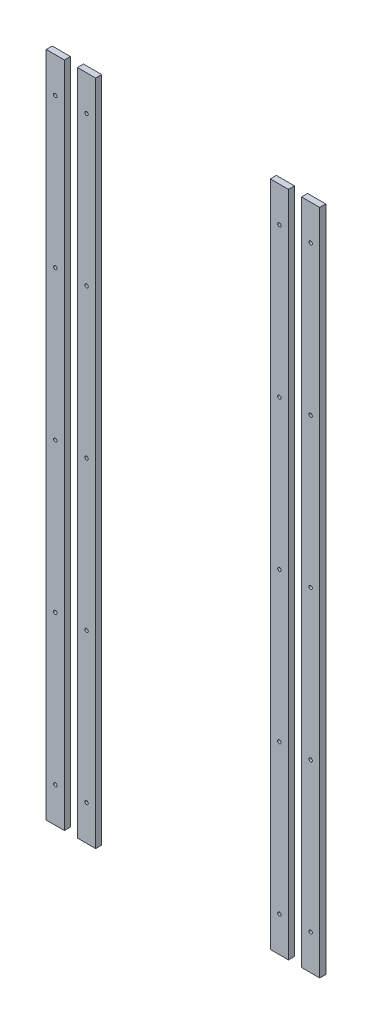
SolidWorks part; units mm, degrees
ref_plane "Спереди" through (0, 0, 0) normal (0, 0, 1) x (1, 0, 0)
ref_plane "Сверху" through (0, 0, 0) normal (0, 1, 0) x (1, 0, 0)
ref_plane "Справа" through (0, 0, 0) normal (1, 0, 0) x (0, 0, -1)
sketch "Четыре_направляющие_эскиз" plane through (0, 0, 0) normal (0, 0, 1) x (1, 0, 0)
  line L0 (315.5, -427) -> (333.5, -427)
  line L1 (333.5, -427) -> (333.5, 235)
  line L2 (333.5, 235) -> (315.5, 235)
  line L3 (315.5, 235) -> (315.5, -427)
  line L4 (346.5, -427) -> (364.5, -427)
  line L5 (364.5, -427) -> (364.5, 235)
  line L6 (364.5, 235) -> (346.5, 235)
  line L7 (346.5, 235) -> (346.5, -427)
  line L8 (537.8, -427) -> (555.8, -427)
  line L9 (555.8, -427) -> (555.8, 235)
  line L10 (555.8, 235) -> (537.8, 235)
  line L11 (537.8, 235) -> (537.8, -427)
  line L12 (568.8, -427) -> (586.8, -427)
  line L13 (586.8, -427) -> (586.8, 235)
  line L14 (586.8, 235) -> (568.8, 235)
  line L15 (568.8, 235) -> (568.8, -427)
  dimension "X001" = 315.5
  dimension "X002" = 333.5
  dimension "X003" = 346.5
  dimension "X004" = 364.5
  dimension "X005" = 537.8
  dimension "X006" = 555.8
  dimension "X007" = 568.8
  dimension "X008" = 586.8
  dimension "Y001" = 427
  dimension "Y002" = 235
extrude "Четыре_направляющие_6мм" add sketch "Четыре_направляющие_эскиз" along normal blind 6
sketch "Крепление_направляющих_М3_эскиз" plane through (0, 0, 0) normal (0, 0, 1) x (1, 0, 0)
  circle A0 centre (324.5, -392) radius 1.7
  circle A1 centre (355.5, -392) radius 1.7
  circle A2 centre (546.8, -392) radius 1.7
  circle A3 centre (577.8, -392) radius 1.7
  dimension "Диаметр001" = 3.4
  dimension "Диаметр002" = 3.4
  dimension "Диаметр003" = 3.4
  dimension "Диаметр004" = 3.4
  dimension "X001" = 324.5
  dimension "X002" = 355.5
  dimension "X003" = 546.8
  dimension "X004" = 577.8
  dimension "Y001" = 392
extrude "Проходы_направляющих_М3" cut sketch "Крепление_направляющих_М3_эскиз" against normal through all and the other way through all
pattern_linear "Массив_крепления_направляющих_5рядов" count 5 spacing 148 along (0, 1, 0) of "Проходы_направляющих_М3"
equation "\"Толщина стенки\"= \"Толщина тонких панелей\""
equation "\"Ширина груза\"= 160"
equation "\"Глубина груза\"= 240"
equation "\"Высота груза\"= 160"
equation "\"Ширина ячейки\"= \"Ширина груза\" + 10"
equation "\"Глубина ячейки\"= \"Глубина груза\" + 10"
equation "\"Высота ячейки\"= \"Высота груза\" + 10 + 13"
equation "\"Колво ячеек ширина\"= 2"
equation "\"Колво ячеек высота\"= 2"
equation "\"Крепление дверцы\"= 5 "
equation "\"Ширина рейки\"= \"Толщина шестерни\""
equation "\"Высота рейки\"= 20"
equation "\"Высота пола\"= 2*\"Толщина тонких панелей\""
equation "\"Колво полозьев\"= 5"
equation "\"Отступ рейки\"= 20"
equation "\"Глубина каретки\"= \"Глубина ячейки\" + 30 + \"Мотор Y высота корпуса\" + 20"
equation "\"Длинна рейки\"= (\"Ширина ячейки\"+\"Толщина вертикальных стенок\"+\"Крепление дверцы\")*\"Колво ячеек ширина\"+\"Ширина ячейки выгрузки\"*\"Колво выгрузки\"+\"Толщина вертикальных стенок\"+2*\"Отступ крепления мотора фиксации\"-\"Крепление дверцы\"*\"Колво ячеек ширина\""
equation "\"Отступ шпильки\"= 26"
equation "\"Диаметр шпильки\"= 5"
equation "\"Длинна шпильки\"= (\"Высота ячейки\"+\"Толщина горизонтальных плит\"+\"Высота пола\")*\"Колво ячеек высота\"+2*(\"Толщина горизонтальных плит\"+\"Отступ рейки\")"
equation "\"Ширина пластины\"= 50  "
equation "\"Высота зона выгрузки\"= \"Высота ячейки\" * 2 + \"Толщина стенки\" * 2"
equation "\"Колво выгрузки\"= 1"
equation "\"Ширина ячейки выгрузки\"= \"Ширина ячейки\"+\"Толщина вертикальных стенок\"+2*\"Отступ крепления мотора фиксации\""
equation "\"Отступ крепления мотора фиксации\"= (\"Ширина пластины\"+20-\"Толщина вертикальных стенок\")/2"
equation "\"Мотор X ширина корпуса\"= 42.3"
equation "\"Мотор X высота корпуса\"= 42.3"
equation "\"Мотор X длина корпуса\"= 40"
equation "\"Мотор X вылет вала\"= 19.8"
equation "\"Мотор Y ширина корпуса\"= 42.3"
equation "\"Мотор Y высота корпуса\"= 42.3"
equation "\"Мотор Y длина корпуса\"= 48"
equation "\"Мотор Y вылет вала\"= 30"
equation "\"Мотор Z ширина корпуса\"= 42"
equation "\"Мотор Z высота корпуса\"= 42"
equation "\"Мотор Z длина корпуса\"= 40"
equation "\"Мотор Z вылет вала\"= 23"
equation "\"Мотор диаметр вала ПРЕДВ\"= 5"
equation "\"Мотор шаг крепления ПРЕДВ\"= 31"
equation "\"Мотор диаметр отверстий ПРЕДВ\"= 3"
equation "\"Мотор глубина отверстий ПРЕДВ\"= 4.5"
equation "\"Мотор диаметр буртика ПРЕДВ\"= 22"
equation "\"Мотор высота буртика ПРЕДВ\"= 2"
equation "\"Мотор диаметр шкива ПРЕДВ\"= 16"
equation "\"Мотор длина шкива ПРЕДВ\"= 12"
equation "\"Мотор отступ шкива ПРЕДВ\"= 5"
equation "\"Мотор X шаг градусов\"= 1.8"
equation "\"Мотор Y шаг градусов\"= 1.8"
equation "\"Мотор Z шаг градусов\"= 1.8"
equation "\"Мотор Y диаметр ротора\"= 25.78"
equation "\"Толщина шестерни\"= 10"
equation "\"Толщина тонких панелей\"= 6"
equation "\"Толщина вертикальных стенок\"= 6"
equation "\"Толщина горизонтальных плит\"= 6"
equation "\"Базовая высота корпуса\"= (\"Высота ячейки\"+\"Толщина тонких панелей\"+\"Высота пола\")*\"Колво ячеек высота\"+6*\"Толщина тонких панелей\"+\"Мотор X ширина корпуса\"+\"Мотор Y ширина корпуса\"+75"
equation "\"Высота корпуса\"= (\"Высота ячейки\"+\"Толщина горизонтальных плит\"+\"Высота пола\")*\"Колво ячеек высота\"+2*\"Толщина горизонтальных плит\"+4*\"Толщина тонких панелей\"+\"Мотор X ширина корпуса\"+\"Мотор Y ширина корпуса\"+75"
equation "\"Смещение центра корпуса\"= (\"Высота корпуса\"-\"Базовая высота корпуса\")/2-(\"Толщина горизонтальных плит\"-\"Толщина тонких панелей\")"
equation "\"Отметка пола\"= -\"Базовая высота корпуса\"/2+\"Толщина тонких панелей\""
equation "\"Отметка потолка\"= \"Отметка пола\"+\"Высота корпуса\"-2*\"Толщина горизонтальных плит\""
equation "\"Отметка верхней полки\"= \"Отметка потолка\"-(28+\"Толщина тонких панелей\")-\"Высота ячейки\"-\"Высота пола\""
equation "\"Отметка нижней полки\"= \"Отметка верхней полки\"-\"Высота ячейки\"-\"Высота пола\"-\"Толщина горизонтальных плит\""
equation "\"Ширина направляющей\"= 18"
equation "\"X001@Четыре_направляющие_эскиз\" = (\"Глубина ячейки\"+74.5-9)"
equation "\"X002@Четыре_направляющие_эскиз\" = (\"Глубина ячейки\"+74.5+9)"
equation "\"X003@Четыре_направляющие_эскиз\" = (\"Глубина ячейки\"+105.5-9)"
equation "\"X004@Четыре_направляющие_эскиз\" = (\"Глубина ячейки\"+105.5+9)"
equation "\"X005@Четыре_направляющие_эскиз\" = (2*\"Глубина ячейки\"+46.8-9)"
equation "\"X006@Четыре_направляющие_эскиз\" = (2*\"Глубина ячейки\"+46.8+9)"
equation "\"X007@Четыре_направляющие_эскиз\" = (2*\"Глубина ячейки\"+77.8-9)"
equation "\"X008@Четыре_направляющие_эскиз\" = (2*\"Глубина ячейки\"+77.8+9)"
equation "\"Y001@Четыре_направляющие_эскиз\" = -(-(2*\"Ширина ячейки\"+87))"
equation "\"Y002@Четыре_направляющие_эскиз\" = (\"Ширина ячейки\"+65)"
equation "\"D1@Четыре_направляющие_6мм\" = \"Толщина тонких панелей\""
equation "\"X001@Крепление_направляющих_М3_эскиз\" = (\"Глубина ячейки\"+74.5)"
equation "\"X002@Крепление_направляющих_М3_эскиз\" = (\"Глубина ячейки\"+105.5)"
equation "\"X003@Крепление_направляющих_М3_эскиз\" = (2*\"Глубина ячейки\"+46.8)"
equation "\"X004@Крепление_направляющих_М3_эскиз\" = (2*\"Глубина ячейки\"+77.8)"
equation "\"Y001@Крепление_направляющих_М3_эскиз\" = -(-(2*\"Ширина ячейки\"+87)+35)"
equation "\"Диаметр001@Крепление_направляющих_М3_эскиз\" = 3.4"
equation "\"Диаметр002@Крепление_направляющих_М3_эскиз\" = 3.4"
equation "\"Диаметр003@Крепление_направляющих_М3_эскиз\" = 3.4"
equation "\"Диаметр004@Крепление_направляющих_М3_эскиз\" = 3.4"
equation "\"D3@Массив_крепления_направляющих_5рядов\" = (\"Длинна рейки\"-70)/4"
